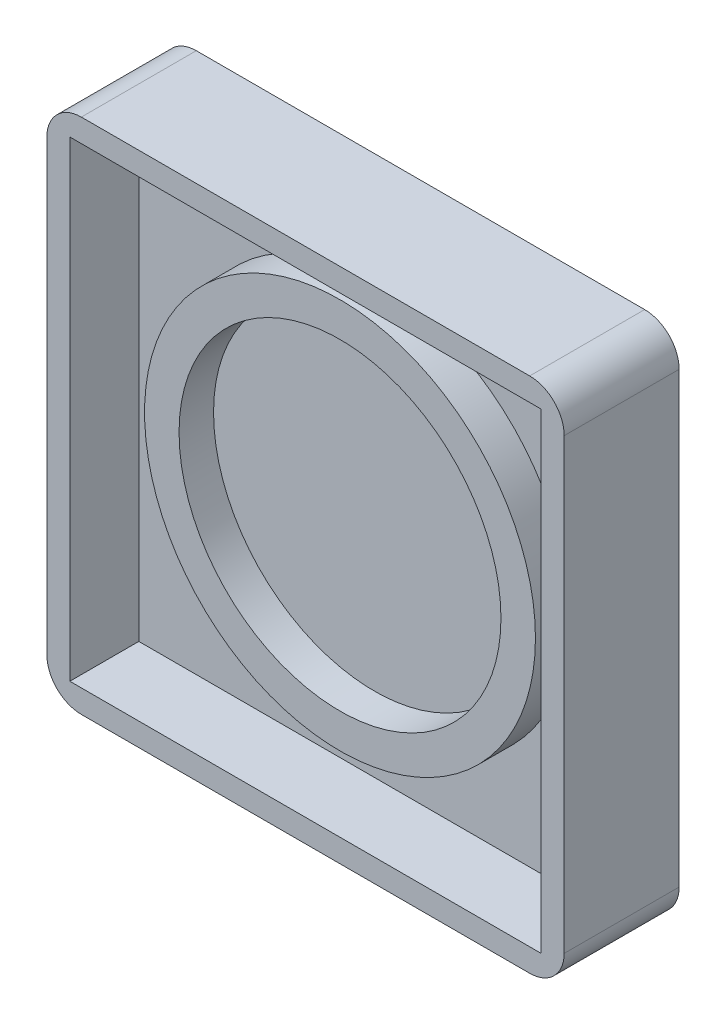
SolidWorks part; units mm, degrees
ref_plane "Front Plane" through (0, 0, 0) normal (0, 0, 1) x (1, 0, 0)
ref_plane "Top Plane" through (0, 0, 0) normal (0, 1, 0) x (1, 0, 0)
ref_plane "Right Plane" through (0, 0, 0) normal (1, 0, 0) x (0, 0, -1)
sketch "Sketch1" plane through (0, 0, 0) normal (0, 0, 1) x (1, 0, 0)
  line L1 (22.5, -22.5) -> (-22.5, -22.5)
  line L2 (22.5, -22.5) -> (22.5, 22.5)
  line L3 (22.5, 22.5) -> (-22.5, 22.5)
  line L4 (-22.5, -22.5) -> (-22.5, 22.5)
  line L5 (22.5, -22.5) -> (-22.5, 22.5) construction
  line L6 (22.5, 22.5) -> (-22.5, -22.5) construction
  point P0 (0, 0)
  dimension "D1" = 45
extrude "Boss-Extrude1" add sketch "Sketch1" along normal blind 10
sketch "Sketch2" plane through (0, 0, 10) normal (0, 0, 1) x (1, 0, 0)
  line L1 (20.5, -20.5) -> (-20.5, -20.5)
  line L2 (20.5, -20.5) -> (20.5, 20.5)
  line L3 (20.5, 20.5) -> (-20.5, 20.5)
  line L4 (-20.5, -20.5) -> (-20.5, 20.5)
  line L5 (20.5, -20.5) -> (-20.5, 20.5) construction
  line L6 (20.5, 20.5) -> (-20.5, -20.5) construction
  point P0 (0, 0)
  dimension "D1" = 41
extrude "Cut-Extrude1" cut sketch "Sketch2" against normal blind 6
sketch "Sketch3" plane through (0, 0, 4) normal (0, 0, 1) x (1, 0, 0)
  circle A0 centre (0, 0) radius 17
  circle A1 centre (0, 0) radius 14
  dimension "D1" = 34
  dimension "D2" = 28
extrude "Boss-Extrude2" add sketch "Sketch3" along normal blind 3
fillet "Fillet2" radius 3 4 edges at (-22.5, -22.5, 5) (22.5, -22.5, 5) (-22.5, 22.5, 5) (22.5, 22.5, 5)
